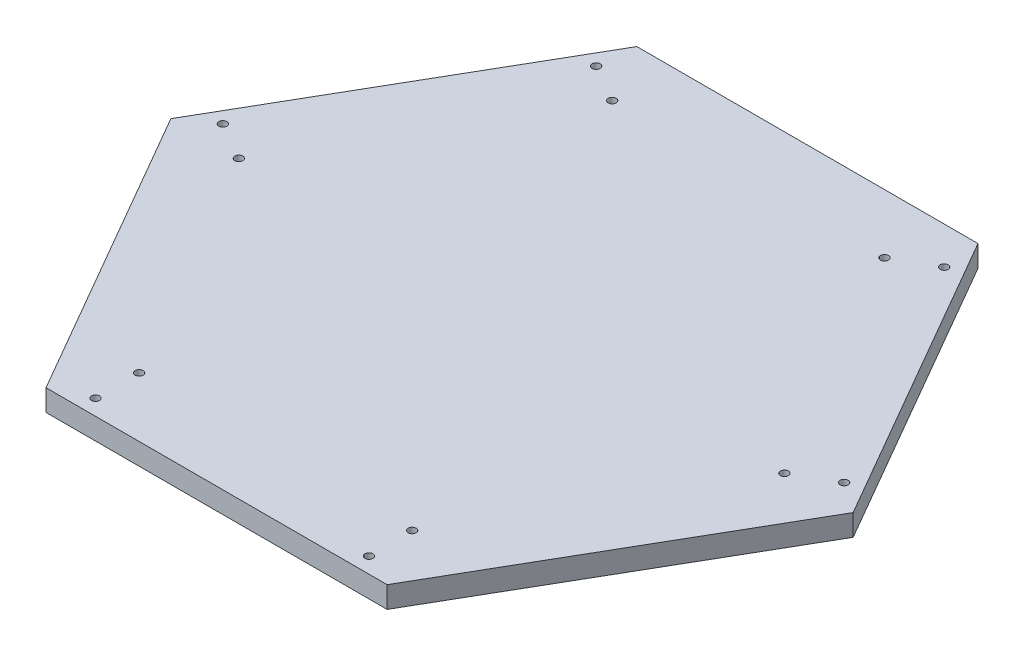
SolidWorks part; units mm, degrees
ref_plane "Front Plane" through (0, 0, 0) normal (0, 0, 1) x (1, 0, 0)
ref_plane "Top Plane" through (0, 0, 0) normal (0, 1, 0) x (1, 0, 0)
ref_plane "Right Plane" through (0, 0, 0) normal (1, 0, 0) x (0, 0, -1)
sketch "Sketch1" plane through (0, 0, 0) normal (0, 1, 0) x (1, 0, 0)
  line L1 (94.0004, -26.0999) -> (30.4004, 84.0585)
  line L2 (30.4004, 84.0585) -> (-96.7996, 84.0585)
  line L3 (-96.7996, 84.0585) -> (-160.3996, -26.0999)
  line L4 (-160.3996, -26.0999) -> (-96.7996, -136.2583)
  line L5 (-96.7996, -136.2583) -> (30.4004, -136.2583)
  line L6 (30.4004, -136.2583) -> (94.0004, -26.0999)
  circle A0 centre (-33.1996, -26.0999) radius 110.1584 construction
  dimension "D1" = 127.2
extrude "Boss-Extrude2" add sketch "Sketch1" along normal blind 8
sketch "Sketch2" plane through (0, 8, 0) normal (0, 1, 0) x (1, 0, 0)
  line L0 (-96.7996, -136.2583) -> (30.4004, -136.2583) construction
  line L1 (94.0004, -26.0999) -> (30.4004, 84.0585) construction
  line L2 (82.6241, -18.0956) -> (68.5079, -26.2456) construction
  line L4 (31.6764, 70.1485) -> (17.5601, 61.9985) construction
  line L5 (-96.7996, 84.0585) -> (-160.3996, -26.0999) construction
  line L6 (-98.0755, 70.1485) -> (-83.9593, 61.9985) construction
  line L7 (-149.0233, -18.0956) -> (-134.9071, -26.2456) construction
  circle A0 centre (17.7804, -130.4083) radius 1.5
  circle A1 centre (-84.1795, -130.4083) radius 1.5
  circle A2 centre (-84.2214, -114.1084) radius 1.5
  circle A3 centre (17.5667, -114.1097) radius 1.5
  circle A4 centre (82.6241, -18.0956) radius 1.5
  circle A5 centre (68.5079, -26.2456) radius 1.5
  circle A6 centre (31.6764, 70.1485) radius 1.5
  circle A7 centre (17.5601, 61.9985) radius 1.5
  circle A8 centre (-98.0755, 70.1485) radius 1.5
  circle A9 centre (-83.9593, 61.9985) radius 1.5
  circle A10 centre (-149.0233, -18.0956) radius 1.5
  circle A11 centre (-134.9071, -26.2456) radius 1.5
  dimension "D1" = 5.85
  dimension "D2" = 3
  dimension "D3" = 13.91
  dimension "D4" = 3
  dimension "D5" = 5.85
  dimension "D6" = 3
  dimension "D7" = 16.3
  dimension "D8" = 3
  dimension "D9" = 3
  dimension "D10" = 16.3
  dimension "D11" = 5.85
  dimension "D12" = 13.91
  dimension "D13" = 13.91
  dimension "D14" = 16.3
  dimension "D15" = 3
  dimension "D16" = 5.85
  dimension "D17" = 13.91
  dimension "D18" = 3
  dimension "D20" = 3
  dimension "D21" = 5.85
  dimension "D22" = 13.91
  dimension "D23" = 3
  dimension "D25" = 3
  dimension "D26" = 5.85
  dimension "D27" = 13.91
  dimension "D28" = 3
  dimension "D30" = 3
  dimension "D19" = 16.3
  dimension "D24" = 16.3
  dimension "D29" = 16.3
extrude "Cut-Extrude1" cut sketch "Sketch2" against normal through all
